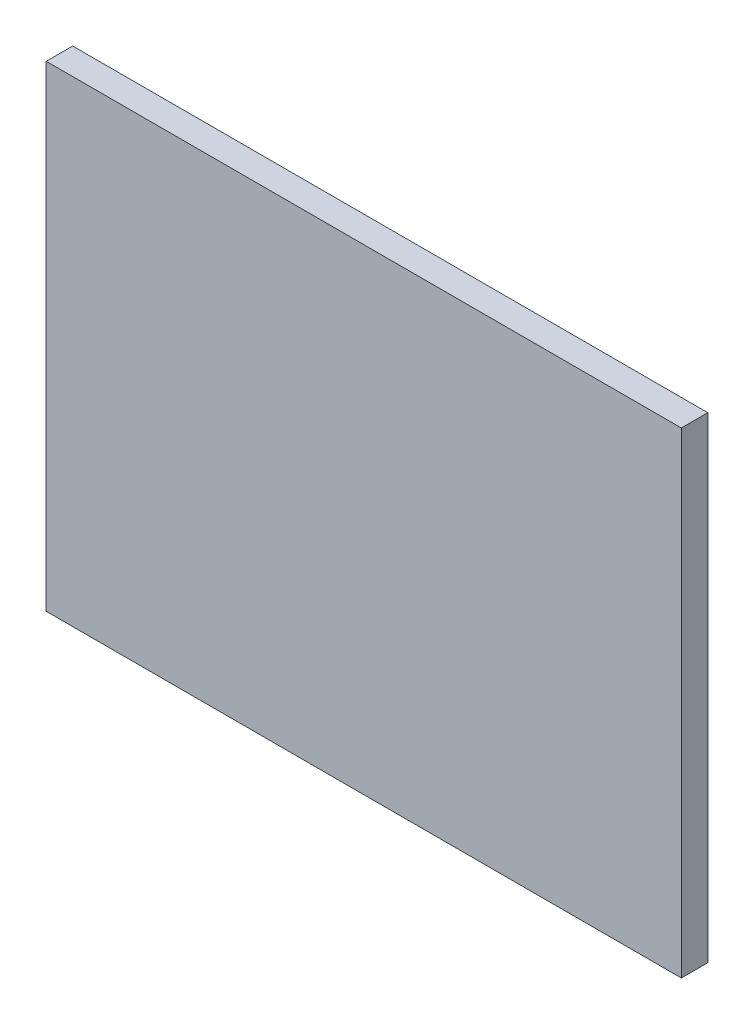
SolidWorks part; units mm, degrees
ref_plane "Front Plane" through (0, 0, 0) normal (0, 0, 1) x (1, 0, 0)
ref_plane "Top Plane" through (0, 0, 0) normal (0, 1, 0) x (1, 0, 0)
ref_plane "Right Plane" through (0, 0, 0) normal (1, 0, 0) x (0, 0, -1)
sketch "Sketch1" plane through (0, 0, 0) normal (0, 0, 1) x (1, 0, 0)
  line L1 (457.2, 0) -> (-152.4, 0)
  line L2 (457.2, 0) -> (457.2, 457.2)
  line L3 (457.2, 457.2) -> (-152.4, 457.2)
  line L4 (-152.4, 0) -> (-152.4, 457.2)
extrude "Boss-Extrude1" add sketch "Sketch1" along normal blind 25.4
